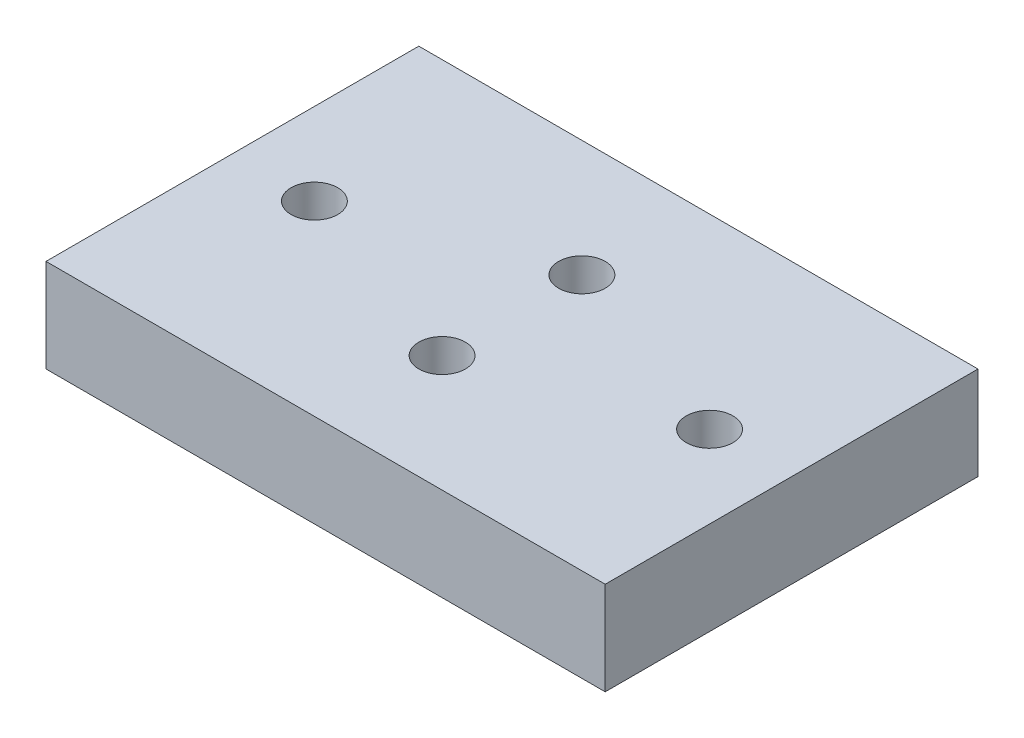
SolidWorks part; units mm, degrees
ref_plane "Front Plane" through (0, 0, 0) normal (0, 0, 1) x (1, 0, 0)
ref_plane "Top Plane" through (0, 0, 0) normal (0, 1, 0) x (1, 0, 0)
ref_plane "Right Plane" through (0, 0, 0) normal (1, 0, 0) x (0, 0, -1)
sketch "Sketch1" plane through (0, 0, 0) normal (0, 1, 0) x (1, 0, 0)
  line L0 (0, -20) -> (60, -20) construction
  line L2 (0, 0) -> (0, -40)
  line L3 (0, -40) -> (60, -40)
  line L4 (60, 0) -> (60, -40)
  line L5 (60, -20) -> (30, -40) construction
  line L6 (30, -40) -> (30, 0) construction
  line L7 (0, 0) -> (60, 0)
  circle A0 centre (51.2, -20) radius 2.5
  circle A1 centre (8.8, -20) radius 2.5
  circle A2 centre (30, -27.5) radius 2.5
  circle A3 centre (30, -12.5) radius 2.5
  dimension "D3" = 5
  dimension "D5" = 5
  dimension "D1" = 60
  dimension "D2" = 40
  dimension "D4" = 21.2
  dimension "D6" = 7.5
extrude "Boss-Extrude1" add sketch "Sketch1" along normal blind 10
sketch "Sketch3" plane through (0, 0, 40) normal (0, 0, 1) x (1, 0, 0)
  line L0 (60, 10) -> (60, 0) construction
  line L2 (0, 10) -> (60, 10) construction
  circle A0 centre (57.5, 7.5) radius 2.5
  dimension "D1" = 5
extrude "Boss-Extrude2" [suppressed] add sketch "Sketch3" along normal blind 10
sketch "Sketch4" plane through (0, 0, 0) normal (0, -1, 0) x (1, 0, 0)
  circle A0 centre (30, 27.5) radius 5
  circle A1 centre (30, 12.5) radius 5
  dimension "D1" = 10
  dimension "D2" = 10
extrude "Cut-Extrude1" cut sketch "Sketch4" against normal blind 5
